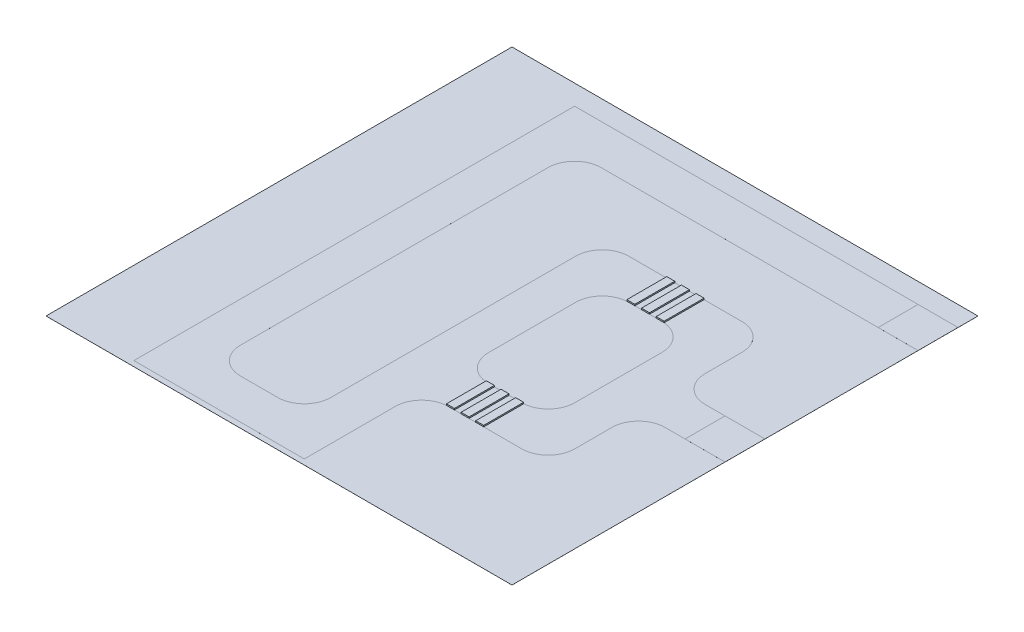
SolidWorks part; units mm, degrees
ref_plane "前视基准面" through (0, 0, 0) normal (0, 0, 1) x (1, 0, 0)
ref_plane "上视基准面" through (0, 0, 0) normal (0, 1, 0) x (1, 0, 0)
ref_plane "右视基准面" through (0, 0, 0) normal (1, 0, 0) x (0, 0, -1)
other "Configuration Table"
sketch "草图2" plane through (0, 0, 0) normal (0, 1, 0) x (1, 0, 0)
  line L1 (-1750, -1750) -> (1750, -1750)
  line L2 (-1750, -1750) -> (-1750, 1750)
  line L3 (-1750, 1750) -> (1750, 1750)
  line L4 (1750, -1750) -> (1750, 1750)
  line L5 (-1750, -1750) -> (1750, 1750) construction
  line L6 (-1750, 1750) -> (1750, -1750) construction
  point P0 (0, 0)
  dimension "D1" = 3500
extrude "凸台-拉伸1" add sketch "草图2" along normal blind 0.1 contours L2 L1 L4 L3
sketch "草图3" plane through (0, 0, 0) normal (0, 1, 0) x (1, 0, 0)
  line L0 (1750, 1600) -> (-1130, 1600)
  line L1 (1750, -1750) -> (1750, 1750) construction
  line L2 (-1130, 1600) -> (-1130, -1710)
  line L3 (-1789.2705, 0) -> (2214.3775, 0) construction
  line L4 (-1130, -1710) -> (150, -1710)
  line L6 (350, -827.5) -> (900, -827.5)
  line L7 (1100, -627.5) -> (1100, -350)
  line L8 (1300, -150) -> (1750, -150)
  line L9 (1750, -150) -> (1750, 150)
  line L10 (1750, 150) -> (1300, 150)
  line L11 (1100, 350) -> (1100, 627.5)
  line L12 (900, 827.5) -> (50, 827.5)
  line L13 (-150, 627.5) -> (-150, -1210)
  line L14 (-350, -1410) -> (-630, -1410)
  line L15 (-830, -1210) -> (-830, 1100)
  line L16 (-630, 1300) -> (1750, 1300)
  line L17 (1750, 1300) -> (1750, 1600)
  line L18 (350, 527.5) -> (600, 527.5)
  line L19 (800, 327.5) -> (800, -327.5)
  line L20 (600, -527.5) -> (350, -527.5)
  line L21 (150, -327.5) -> (150, 327.5)
  line L22 (-1750, 1750) -> (1750, 1750) construction
  line L23 (-1750, -1750) -> (-1750, 1750) construction
  line L24 (150, -1027.5) -> (150, -1710)
  arc A0 (350, 527.5) -> (150, 327.5) centre (350, 327.5) ccw
  arc A1 (350, -527.5) -> (150, -327.5) centre (350, -327.5) cw
  arc A2 (600, 527.5) -> (800, 327.5) centre (600, 327.5) cw
  arc A3 (800, -327.5) -> (600, -527.5) centre (600, -327.5) cw
  arc A4 (50, 827.5) -> (-150, 627.5) centre (50, 627.5) ccw
  arc A5 (-830, 1100) -> (-630, 1300) centre (-630, 1100) cw
  arc A6 (-630, -1410) -> (-830, -1210) centre (-630, -1210) cw
  arc A7 (-150, -1210) -> (-350, -1410) centre (-350, -1210) cw
  arc A8 (150, -1027.5) -> (350, -827.5) centre (350, -1027.5) cw
  arc A9 (1300, 150) -> (1100, 350) centre (1300, 350) cw
  arc A10 (1100, -350) -> (1300, -150) centre (1300, -350) cw
  arc A11 (900, -827.5) -> (1100, -627.5) centre (900, -627.5) ccw
  arc A12 (1100, 627.5) -> (900, 827.5) centre (900, 627.5) ccw
  point P27 (800, 0)
  point P30 (1750, 0)
  dimension "D14" = 200
  dimension "D15" = 200
  dimension "D16" = 200
  dimension "D1" = 300
  dimension "D2" = 3310
  dimension "D3" = 620
  dimension "D4" = 1280
  dimension "D5" = 1655
  dimension "D6" = 300
  dimension "D7" = 150
  dimension "D8" = 300
  dimension "D9" = 300
  dimension "D10" = 300
  dimension "D11" = 300
  dimension "D13" = 300
extrude "凸台-拉伸3" add sketch "草图3" along normal blind 0.11
sketch "草图4" plane through (0, 0.1, 0) normal (0, 1, 0) x (1, 0, 0)
  line L0 (1750, 1300) -> (-630, 1300) construction
  line L1 (1750, 1600) -> (1450, 1600)
  line L2 (1750, 1600) -> (1750, 1300)
  line L3 (1750, 1300) -> (1450, 1300)
  line L4 (1450, 1600) -> (1450, 1300)
extrude "凸台-拉伸4" add sketch "草图4" along normal blind 0.12
sketch "草图5" plane through (0, 0.1, 0) normal (0, 1, 0) x (1, 0, 0)
  line L0 (1750, -150) -> (1300, -150) construction
  line L1 (1750, 150) -> (1450, 150)
  line L2 (1750, 150) -> (1750, -150)
  line L3 (1750, -150) -> (1450, -150)
  line L4 (1450, 150) -> (1450, -150)
extrude "凸台-拉伸5" add sketch "草图5" along normal blind 0.13
sketch "草图6" plane through (-425.8227, 0.1, 0) normal (0, 1, 0) x (1, 0, 0)
  line L0 (1525.8227, 350) -> (1525.8227, 627.5) construction
  line L1 (870.8227, 827.5) -> (930.8227, 827.5)
  line L2 (870.8227, 827.5) -> (870.8227, 527.5)
  line L3 (870.8227, 527.5) -> (930.8227, 527.5)
  line L4 (930.8227, 827.5) -> (930.8227, 527.5)
  line L5 (475.8227, 827.5) -> (1325.8227, 827.5) construction
  line L6 (1040.8227, 827.5) -> (1040.8227, 527.5)
  line L7 (980.8227, 527.5) -> (1040.8227, 527.5)
  line L8 (980.8227, 827.5) -> (1040.8227, 827.5)
  line L9 (980.8227, 827.5) -> (980.8227, 527.5)
  line L10 (900.8227, 827.5) -> (900.8227, 527.5) construction
  line L11 (820.8227, 827.5) -> (760.8227, 827.5)
  line L12 (760.8227, 827.5) -> (760.8227, 527.5)
  line L13 (820.8227, 527.5) -> (760.8227, 527.5)
  line L14 (820.8227, 827.5) -> (820.8227, 527.5)
  point P7 (900.8227, 827.5)
  dimension "D1" = 300
  dimension "D2" = 60
  dimension "D3" = 625
  dimension "D5" = 50
  dimension "D4" = 2
extrude "凸台-拉伸6" add sketch "草图6" along normal blind 10 separate body
mirror "镜向1" about plane through (0, 0, 0) normal (0, 0, 1) of "凸台-拉伸6"
sketch "草图7" plane through (0, 0.1, 0) normal (0, 1, 0) x (1, 0, 0)
  line L0 (-1750, 1750) -> (1750, 1750) construction
  line L1 (-200, 1750) -> (200, 1750)
  line L2 (-200, 1750) -> (-200, 1600)
  line L3 (-200, 1600) -> (200, 1600)
  line L4 (200, 1750) -> (200, 1600)
  line L5 (-1130, 1600) -> (1750, 1600) construction
  line L6 (-1130, 1600) -> (-1130, -1710) construction
  dimension "D1" = 930
  dimension "D2" = 400
extrude "凸台-拉伸7" [suppressed] add sketch "草图7" along normal blind 100
sketch "草图8" plane through (0, 0.1, 0) normal (0, 1, 0) x (1, 0, 0)
  line L0 (-1750, -1750) -> (-1750, 1750) construction
  line L1 (-1564.5864, 1309.9767) -> (-1750, 1309.9767)
  line L2 (-1564.5864, 1309.9767) -> (-1564.5864, 809.9767)
  line L3 (-1564.5864, 809.9767) -> (-1750, 809.9767)
  line L4 (-1750, 1309.9767) -> (-1750, 809.9767)
  dimension "D1" = 500
extrude "凸台-拉伸8" [suppressed] add sketch "草图8" along normal blind 65
sketch "草图9" plane through (0, 0.1, 0) normal (0, 1, 0) x (1, 0, 0)
  line L0 (-1130, -1710) -> (-1130, 1600) construction
  line L1 (-1130, -645) -> (-1225, -645)
  line L2 (-1130, -645) -> (-1130, -1145)
  line L3 (-1130, -1145) -> (-1225, -1145)
  line L4 (-1225, -645) -> (-1225, -1145)
  line L5 (-1750, -1750) -> (1750, -1750) construction
  dimension "D1" = 500
  dimension "D2" = 605
  dimension "D3" = 95
extrude "凸台-拉伸9" [suppressed] add sketch "草图9" along normal blind 0.14
sketch "草图10" [suppressed] plane through (0, 65.1, 0) normal (0, 1, 0) x (1, 0, 0)
  line L0 (-1750, 1309.9767) -> (-1750, 809.9767) construction
  line L1 (-1750, 1134.9767) -> (-1564.5864, 1134.9767)
  line L2 (-1750, 1134.9767) -> (-1750, 984.9767)
  line L3 (-1750, 984.9767) -> (-1564.5864, 984.9767)
  line L4 (-1564.5864, 1134.9767) -> (-1564.5864, 984.9767)
  line L5 (-1564.5864, 809.9767) -> (-1564.5864, 1309.9767) construction
  line L6 (-1750, 1059.9767) -> (-1564.5864, 1059.9767) construction
  line L7 (-1750, 972.4767) -> (-1564.5864, 972.4767)
  line L8 (-1564.5864, 972.4767) -> (-1564.5864, 822.4767)
  line L9 (-1750, 822.4767) -> (-1564.5864, 822.4767)
  line L10 (-1750, 809.9767) -> (-1564.5864, 809.9767) construction
  line L11 (-1750, 972.4767) -> (-1750, 822.4767)
  line L12 (-1750, 1147.4767) -> (-1564.5864, 1147.4767)
  line L13 (-1564.5864, 1147.4767) -> (-1564.5864, 1297.4767)
  line L14 (-1750, 1297.4767) -> (-1564.5864, 1297.4767)
  line L15 (-1750, 1147.4767) -> (-1750, 1297.4767)
  point P10 (-1750, 1059.9767)
  dimension "D1" = 150
  dimension "D3" = 12.5
  dimension "D2" = 2
extrude "凸台-拉伸10" [suppressed] add sketch "草图10" along normal blind 0.1
sketch "草图11" [suppressed] plane through (0, 0.24, 0) normal (0, 1, 0) x (1, 0, 0)
  line L0 (-1130, -895) -> (-1225, -895) construction
  line L1 (-1130, -645) -> (-1130, -1145) construction
  line L2 (-1225, -645) -> (-1225, -1145) construction
  circle A0 centre (-1177.5, -895) radius 20
  circle A1 centre (-1177.5, -745) radius 20
  circle A2 centre (-1177.5, -1045) radius 20
  dimension "D1" = 40
  dimension "D3" = 300
  dimension "D2" = 2
extrude "凸台-拉伸11" [suppressed] add sketch "草图11" along normal blind 0.1
